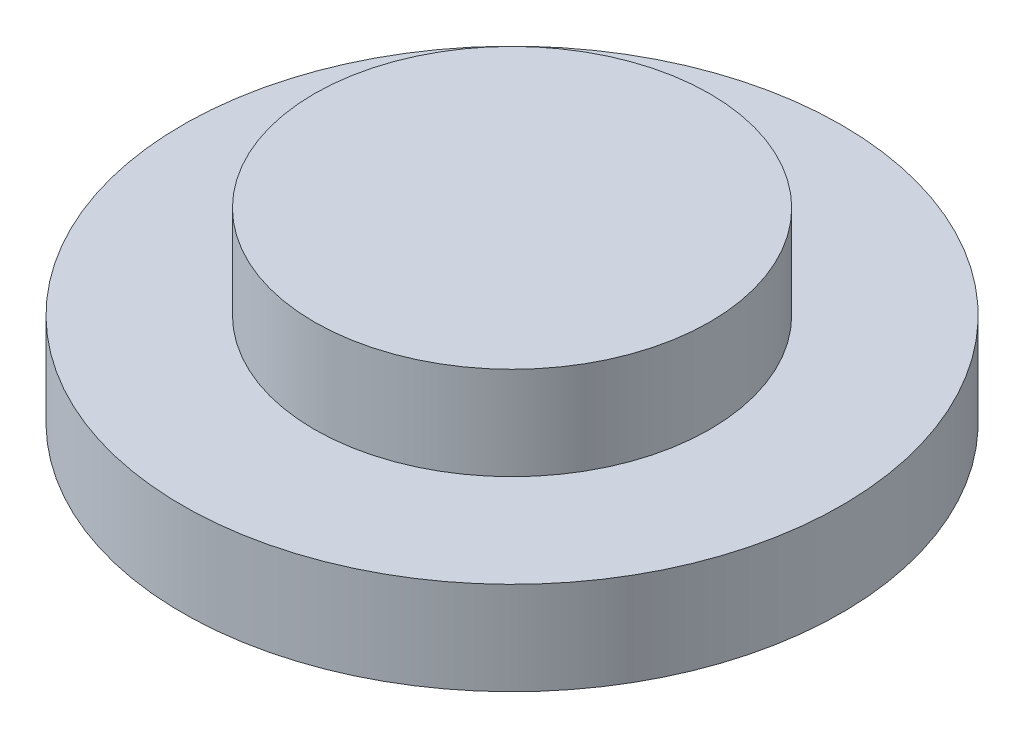
SolidWorks part; units mm, degrees
ref_plane "Front Plane" through (0, 0, 0) normal (0, 0, 1) x (1, 0, 0)
ref_plane "Top Plane" through (0, 0, 0) normal (0, 1, 0) x (1, 0, 0)
ref_plane "Right Plane" through (0, 0, 0) normal (1, 0, 0) x (0, 0, -1)
sketch "Sketch2" plane through (0, 0, 0) normal (0, 0, 1) x (1, 0, 0)
  line L0 (0, 0) -> (0, 25.4)
  line L1 (0, -55) -> (0, 55) construction
  line L2 (0, 25.4) -> (27, 25.4)
  line L3 (27, 25.4) -> (27, 12.7)
  line L4 (27, 12.7) -> (45, 12.7)
  line L5 (45, 12.7) -> (45, 0)
  line L6 (55, 0) -> (-55, 0) construction
  line L7 (45, 0) -> (0, 0)
  dimension "D1" = 25.4
  dimension "D2" = 12.7
  dimension "D3" = 45
  dimension "D4" = 27
revolve "Revolve1" add sketch "Sketch2" angle 360 about L0
sketch "cranksketch" plane through (0, 0, 0) normal (0, -1, 0) x (1, 0, 0)
  line L1 (-24.765, 20) -> (24.765, 20)
  line L2 (-24.765, 20) -> (-24.765, -20)
  line L3 (-24.765, -20) -> (24.765, -20)
  line L4 (24.765, 20) -> (24.765, -20)
  line L5 (-24.765, 20) -> (24.765, -20) construction
  line L6 (-24.765, -20) -> (24.765, 20) construction
  point P0 (0, 0)
  dimension "D1" = 40
  dimension "D2" = 49.53
